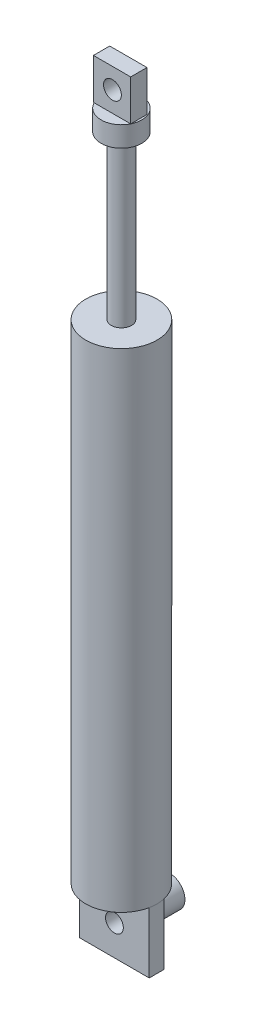
SolidWorks part; units mm, degrees
ref_plane "Front Plane" through (0, 0, 0) normal (0, 0, 1) x (1, 0, 0)
ref_plane "Top Plane" through (0, 0, 0) normal (0, 1, 0) x (1, 0, 0)
ref_plane "Right Plane" through (0, 0, 0) normal (1, 0, 0) x (0, 0, -1)
sketch "Sketch1" plane through (0, 0, 0) normal (0, 1, 0) x (1, 0, 0)
  circle A0 centre (0, 0) radius 11.1125
  dimension "D1" = 22.225
extrude "Boss-Extrude1" add sketch "Sketch1" along normal blind 152.4
sketch "Sketch2" plane through (0, 152.4, 0) normal (0, 1, 0) x (1, 0, 0)
  circle A0 centre (0, 0) radius 3.175
  dimension "D1" = 6.35
extrude "Boss-Extrude2" add sketch "Sketch2" along normal blind 50.8
sketch "Sketch3" plane through (0, 0, 0) normal (0, -1, 0) x (1, 0, 0)
  line L1 (10.8608, -2.352) -> (-10.8968, -2.352)
  line L2 (10.8608, -2.352) -> (10.8608, 2.179)
  line L3 (10.8608, 2.179) -> (-10.8968, 2.179)
  line L4 (-10.8968, -2.352) -> (-10.8968, 2.179)
  circle A0 centre (0, 0) radius 11.1125 construction
extrude "Boss-Extrude3" add sketch "Sketch3" along normal blind 19.05
sketch "Sketch4" plane through (0, 0, 2.179) normal (0, 0, 1) x (1, 0, 0)
  line L0 (10.8608, -19.05) -> (-10.8968, -19.05) construction
  circle A0 centre (0, -9.525) radius 2.7781
  point P2 (-0.018, -19.05)
  dimension "D1" = 5.5562
  dimension "D2" = 9.525
extrude "Cut-Extrude1" cut sketch "Sketch4" against normal blind 19.05
sketch "Sketch5" plane through (0, 0, -2.352) normal (0, 0, -1) x (-1, 0, 0)
  circle A0 centre (0, -9.525) radius 2.7781
  circle A1 centre (0, -9.525) radius 4.7625
  dimension "D1" = 9.525
extrude "Boss-Extrude4" add sketch "Sketch5" along normal blind 12.7
sketch "Sketch6" plane through (0, 203.2, 0) normal (0, 1, 0) x (1, 0, 0)
  circle A0 centre (0, 0) radius 6.35
  dimension "D1" = 12.7
extrude "Boss-Extrude5" add sketch "Sketch6" along normal blind 6.35
sketch "Sketch7" plane through (0, 209.55, 0) normal (0, 1, 0) x (1, 0, 0)
  line L1 (5.6961, -2.8066) -> (-5.9291, -2.8066)
  line L2 (5.6961, -2.8066) -> (5.6961, 2.2734)
  line L3 (5.6961, 2.2734) -> (-5.9291, 2.2734)
  line L4 (-5.9291, -2.8066) -> (-5.9291, 2.2734)
  circle A0 centre (0, 0) radius 6.35 construction
  dimension "D1" = 5.08
extrude "Boss-Extrude6" add sketch "Sketch7" along normal blind 12.7
sketch "Sketch8" plane through (0, 0, 2.8066) normal (0, 0, 1) x (1, 0, 0)
  line L0 (-5.6961, 209.55) -> (5.6961, 209.55) construction
  circle A0 centre (0, 215.9) radius 2.7781
  dimension "D1" = 5.5562
  dimension "D2" = 6.35
extrude "Cut-Extrude2" cut sketch "Sketch8" against normal blind 12.7
